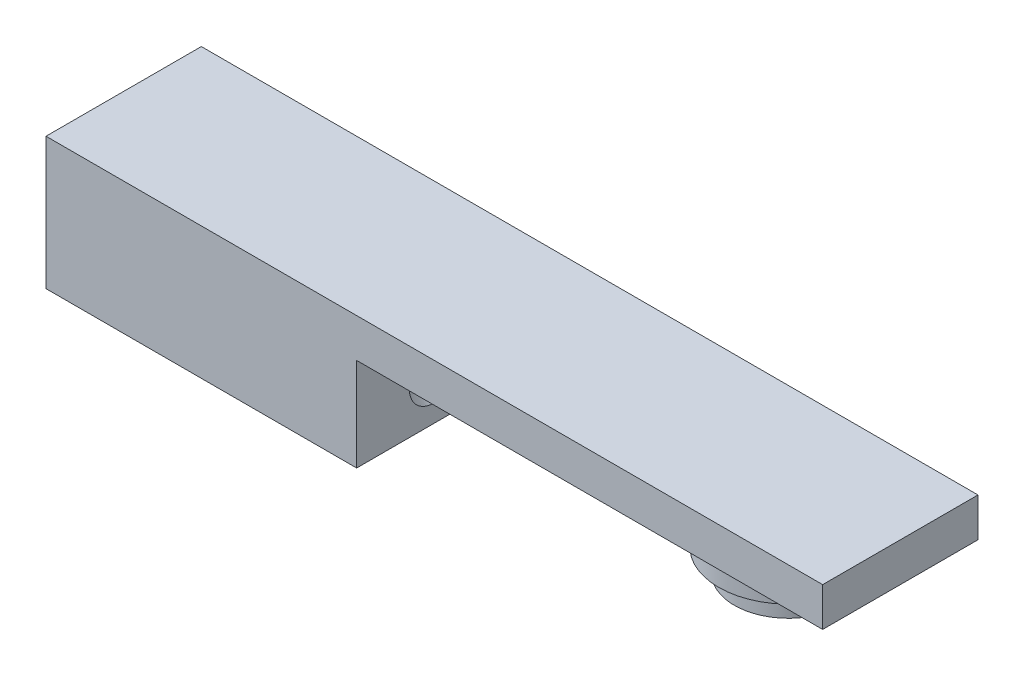
SolidWorks part; units mm, degrees
ref_plane "Спереди" through (0, 0, 0) normal (0, 0, 1) x (1, 0, 0)
ref_plane "Сверху" through (0, 0, 0) normal (0, 1, 0) x (1, 0, 0)
ref_plane "Справа" through (0, 0, 0) normal (1, 0, 0) x (0, 0, -1)
sketch "Эскиз1" plane through (0, 0, 0) normal (1, 0, 0) x (0, 0, -1)
  line L1 (-37.7241, 2.361) -> (-17.7241, 2.361)
  line L2 (-37.7241, 2.361) -> (-37.7241, 19.361)
  line L3 (-37.7241, 19.361) -> (-17.7241, 19.361)
  line L4 (-17.7241, 2.361) -> (-17.7241, 19.361)
  dimension "D1" = 17
  dimension "D2" = 20
extrude "Бобышка-Вытянуть1" add sketch "Эскиз1" along normal blind 40
sketch "Эскиз2" plane through (40, 0, 0) normal (1, 0, 0) x (0, 0, -1)
  line L0 (-27.7241, 19.361) -> (-27.7241, -9.226) construction
  line L1 (-17.7241, 19.361) -> (-37.7241, 19.361) construction
  line L3 (-17.7241, 2.361) -> (-17.7241, 19.361) construction
  line L4 (-46.9913, 14.361) -> (-2.5903, 14.361) construction
  line L6 (-37.7241, 19.361) -> (-17.7241, 19.361)
  line L7 (-37.7241, 19.361) -> (-37.7241, 14.361)
  line L8 (-37.7241, 14.361) -> (-17.7241, 14.361)
  line L9 (-17.7241, 19.361) -> (-17.7241, 14.361)
  dimension "D1" = 5
  dimension "D2" = 20
extrude "Бобышка-Вытянуть2" add sketch "Эскиз2" along normal blind 60
sketch "Эскиз3" plane through (0, 14.361, 0) normal (0, -1, 0) x (1, 0, 0)
  line L0 (100, 27.7241) -> (37.0686, 27.7241) construction
  line L1 (100, 37.7241) -> (100, 17.7241) construction
  circle A0 centre (85.6202, 27.7241) radius 9
extrude "Бобышка-Вытянуть3" add sketch "Эскиз3" along normal blind 3
sketch "Эскиз4" plane through (0, 11.361, 0) normal (0, -1, 0) x (1, 0, 0)
  line L0 (94.6202, 27.7241) -> (69.3301, 27.7241) construction
  line L1 (85.6202, 27.7241) -> (85.6202, 37.9572) construction
  circle A0 centre (85.6202, 27.7241) radius 9 construction
  circle A1 centre (85.6202, 27.7241) radius 9 construction
  circle A2 centre (85.6202, 27.7241) radius 7
extrude "Бобышка-Вытянуть4" add sketch "Эскиз4" along normal blind 3
hole_wizard "Зенковка для винта с полупотайной головкой M32" positions "Эскиз14" profile "Эскиз15" countersink size "M3" standard "ISO"
sketch "Эскиз14" plane through (40, 0, 0) normal (1, 0, 0) x (0, 0, -1)
  point P0 (-27.791, 7.7841)
sketch "Эскиз15" plane through (40, 7.7841, 27.791) normal (0, 1, 0) x (0, 0, -1)
  line L0 (0, 0) -> (0, 40)
  line L1 (0, 40) -> (1.7, 40)
  line L2 (1.7, 40) -> (1.7, 1.45)
  line L3 (1.7, 1.45) -> (3.15, 0)
  line L5 (3.15, 0) -> (0, 0)
  line L6 (-1.7, 1.45) -> (-3.15, 0) construction
  line L11 (0, -6.35) -> (0, 107.95) construction
  dimension "Диаметр сквозного отверстия" = 3.4
  dimension "Глубина сквозного отверстия" = 40
  dimension "Диаметр передней зенковки" = 6.3
  dimension "Угол передней зенковки" = 90
